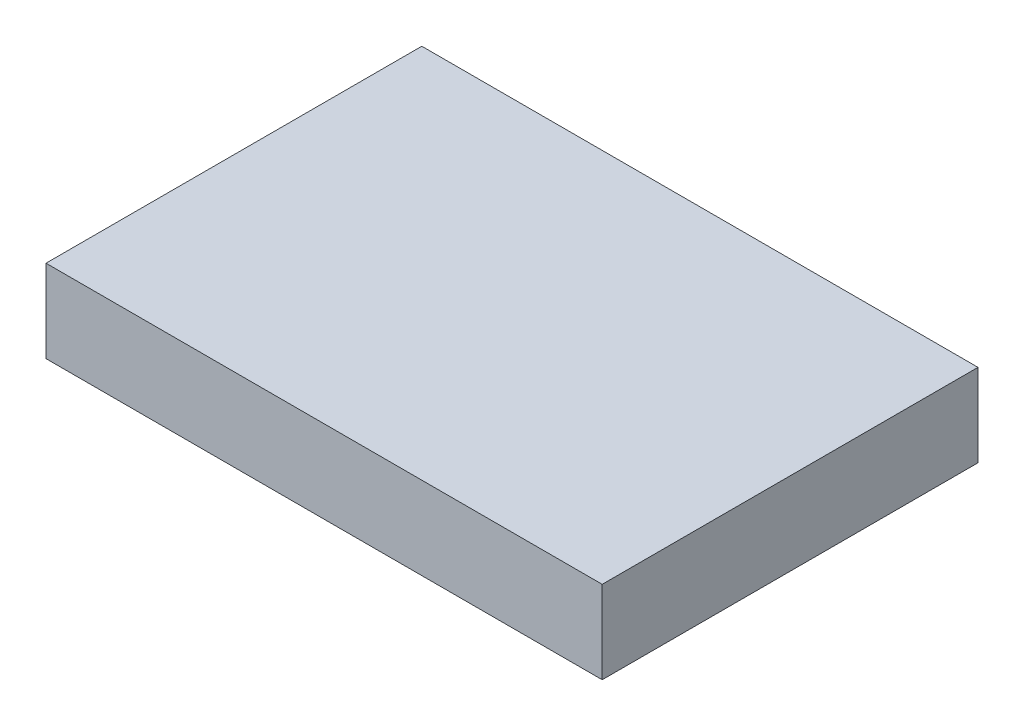
SolidWorks part; units mm, degrees
ref_plane "Front Plane" through (0, 0, 0) normal (0, 0, 1) x (1, 0, 0)
ref_plane "Top Plane" through (0, 0, 0) normal (0, 1, 0) x (1, 0, 0)
ref_plane "Right Plane" through (0, 0, 0) normal (1, 0, 0) x (0, 0, -1)
sketch "Sketch1" plane through (0, 0, 0) normal (0, 1, 0) x (1, 0, 0)
  line L1 (-18.5, -12.5) -> (18.5, -12.5)
  line L2 (-18.5, -12.5) -> (-18.5, 12.5)
  line L3 (-18.5, 12.5) -> (18.5, 12.5)
  line L4 (18.5, -12.5) -> (18.5, 12.5)
  line L5 (-18.5, -12.5) -> (18.5, 12.5) construction
  line L6 (-18.5, 12.5) -> (18.5, -12.5) construction
  point P0 (0, 0)
  dimension "D1" = 37
  dimension "D2" = 25
extrude "Boss-Extrude1" add sketch "Sketch1" along normal blind 5.5
